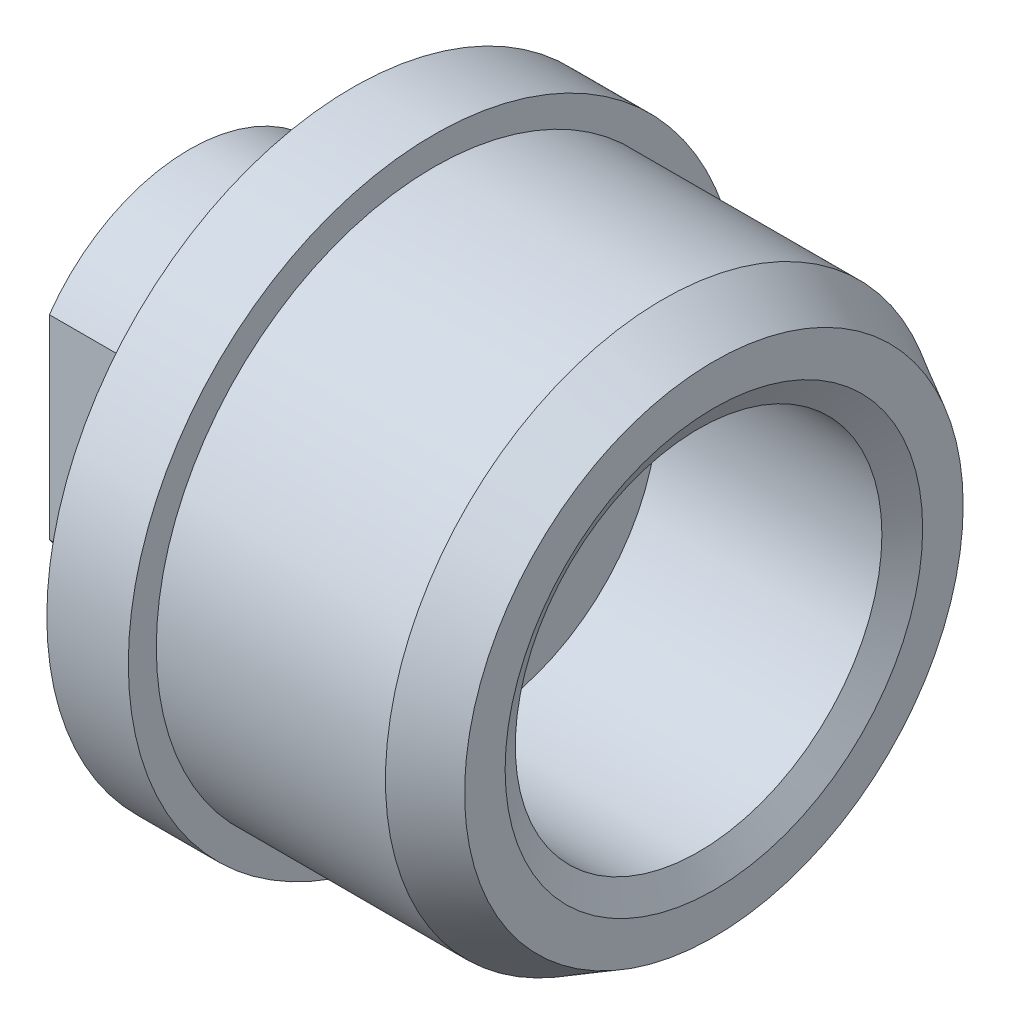
SolidWorks part; units mm, degrees
material "Brass"
ref_plane "Front Plane" through (0, 0, 0) normal (0, 0, 1) x (1, 0, 0)
ref_plane "Top Plane" through (0, 0, 0) normal (0, 1, 0) x (1, 0, 0)
ref_plane "Right Plane" through (0, 0, 0) normal (1, 0, 0) x (0, 0, -1)
sketch "Sketch1" plane through (0, 0, 0) normal (1, 0, 0) x (0, 0, -1)
  circle A0 centre (0, 0) radius 6.9215
  dimension "D1" = 13.843
extrude "Boss-Extrude1" add sketch "Sketch1" against normal blind 6.985
cosmetic thread "Cosmetic Thread5" parameters "D2"=11.1887
sketch "Sketch2" plane through (-6.985, 0, 0) normal (-1, 0, 0) x (0, 0, 1)
  circle A0 centre (0, 0) radius 7.62
  dimension "D1" = 15.24
extrude "Boss-Extrude2" add sketch "Sketch2" along normal blind 2.032
sketch "Sketch3" plane through (-9.017, 0, 0) normal (-1, 0, 0) x (0, 0, 1)
  circle A0 centre (0, 0) radius 4.2545
  dimension "D1" = 8.509
extrude "Boss-Extrude3" add sketch "Sketch3" along normal blind 4.064
sketch "Sketch4" plane through (-13.081, 0, 0) normal (-1, 0, 0) x (0, 0, 1)
  line L0 (-3.4925, 0) -> (3.4925, 0) construction
  line L1 (-3.4925, 2.4297) -> (-3.4925, -2.4297)
  line L2 (3.4925, 2.4297) -> (3.4925, -2.4297)
  circle A0 centre (0, 0) radius 4.2545 construction
  circle A1 centre (0, 0) radius 4.2545 construction
  circle M1 centre (0, 0) radius 4.2545
  dimension "D1" = 6.985
  dimension "D2" = 3.4925
extrude "Cut-Extrude1" cut sketch "Sketch4" against normal blind 4.064 contours L1 M1 | L2 M1
sketch "Sketch5" plane through (-13.081, 0, 0) normal (-1, 0, 0) x (0, 0, 1)
  circle A0 centre (0, 0) radius 2.032
  dimension "D1" = 4.064
extrude "Cut-Extrude2" cut sketch "Sketch5" against normal through all
sketch "Sketch6" plane through (0, 0, 0) normal (1, 0, 0) x (0, 0, -1)
  circle A0 centre (0, 0) radius 4.572
  dimension "D1" = 9.144
extrude "Cut-Extrude3" cut sketch "Sketch6" against normal blind 5.969
chamfer "Chamfer1" distance 1.27 angle 29 1 edges at (0, 0, -6.9215)
chamfer "Chamfer2" distance 0.635 angle 31 1 edges at (0, 0, -4.572)
